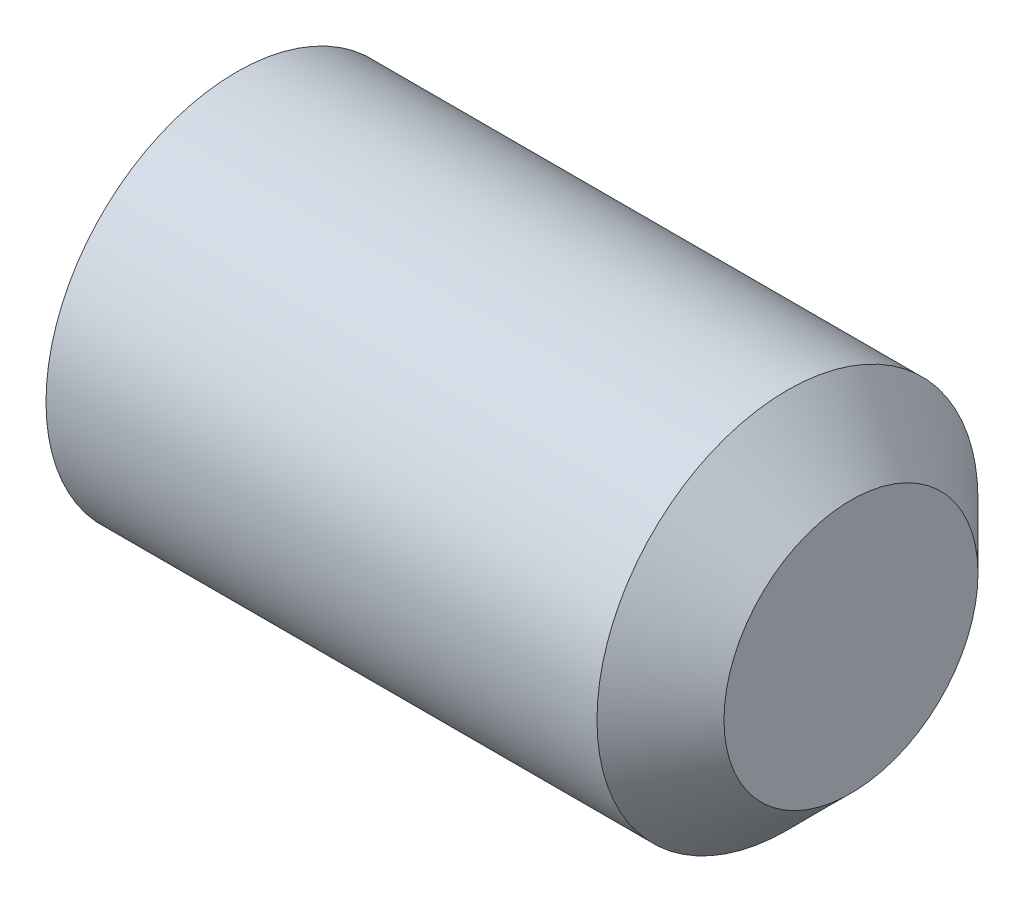
SolidWorks part; units mm, degrees
ref_plane "Plane1" through (0, 0, 0) normal (0, 0, 1) x (1, 0, 0)
ref_plane "Plane2" through (0, 0, 0) normal (0, 1, 0) x (1, 0, 0)
ref_plane "Plane3" through (0, 0, 0) normal (1, 0, 0) x (0, 0, -1)
sketch "BodySke" plane through (0, 0, 0) normal (0, 0, 1) x (1, 0, 0)
  line L0 (0, 0) -> (0, 1.2195)
  line L1 (0, 1.2195) -> (0.1619, 1.5)
  line L2 (0.1619, 1.5) -> (4.5, 1.5)
  line L3 (4.5, 1.5) -> (5, 1)
  line L4 (5, 0) -> (0, 0)
  line L5 (-12.7, 0) -> (88.9, 0) construction
  line L6 (5, 1) -> (5, 0)
  line L7 (5, 1) -> (5, 10.525) construction
  line L8 (0, -1.2195) -> (0.1619, -1.5) construction
  line L9 (0.5, 15.875) -> (0.5, -3.175) construction
  line L10 (4.5, -1.5) -> (5, -1) construction
  dimension "Length" = 5
  dimension "Diameter" = 3
  dimension "Drive_ch_ang" = 60
  dimension "Minor_dia" = 2.439
  dimension "Cup_nose_ang" = 45
  dimension "Cup_dia" = 2
  dimension "Advance" = 0.5
revolve "BaseBody" add sketch "BodySke" angle 360 about L5
cosmetic thread "ThreadCosmetic" [suppressed] parameters "Thread_minor"=2.439
sketch "Sketch2" plane through (0, 0, 0) normal (-1, 0, 0) x (0, 0, 1)
  line L0 (0.433, 0.75) -> (-0.433, 0.75)
  line L1 (-0.433, 0.75) -> (-0.866, 0)
  line L2 (0.433, 0.75) -> (0.866, 0)
  line L3 (0.433, -0.75) -> (0.866, 0)
  line L4 (0.433, -0.75) -> (-0.433, -0.75)
  line L5 (-0.433, -0.75) -> (-0.866, 0)
  dimension "Hex_size" = 1.5
  dimension "D2" = 0.75
  dimension "D3" = 0.75
extrude "Hex" cut sketch "Sketch2" against normal blind 2.1
sketch "Sketch4" plane through (0, 4.7709, -0.5249) normal (-1, 0, 0) x (0, 0, 1)
  line L0 (0.5249, -4.7709) -> (1.3124, -4.7709)
  line L1 (0.5249, -4.7709) -> (6.6732, -1.2211) construction
  line L2 (0.5249, -4.7709) -> (0.9186, -4.0889)
  line L3 (1.153, -4.6137) -> (1.2782, -4.5415)
  line L4 (0.975, -4.3054) -> (1.1002, -4.2332)
  arc A0 (1.153, -4.6137) -> (0.975, -4.3054) centre (0.5249, -4.7709) ccw
  arc A1 (1.3124, -4.7709) -> (1.2782, -4.5415) centre (0.5249, -4.7709) ccw
  arc A2 (0.9186, -4.0889) -> (1.1002, -4.2332) centre (0.5249, -4.7709) cw
  circle A3 centre (0.5249, -4.7709) radius 0.6475 construction
  circle A4 centre (0.5249, -4.7709) radius 0.7875 construction
  dimension "D1" = 30
  dimension "Spline_n_dim" = 1.295
  dimension "Spline_m_dim" = 1.575
  dimension "Spline_a_dim" = 60
  dimension "D3" = 0.178
  dimension "Spline_p_dim" = 0.356
extrude "Spline6" [suppressed] cut sketch "Sketch4" against normal blind 1.2
pattern_circular "CirPattern1" [suppressed] count 6 every 60 about axis through (-12.7, 0, 0) along (1, 0, 0)
sketch "Sketch5" plane through (0, 0.6556, 6.6316) normal (-1, 0, 0) x (0, 0, 1)
  line L0 (-6.6316, -0.6556) -> (-5.8441, -0.6556)
  line L1 (-6.6316, -0.6556) -> (-1.6115, 4.3645) construction
  line L2 (-6.6316, -0.6556) -> (-6.6316, 0.1319)
  line L3 (-6.0479, -0.3236) -> (-5.9633, -0.239)
  line L4 (-6.2996, -0.0719) -> (-6.215, 0.0127)
  line L5 (-6.2996, -0.0719) -> (-6.0479, -0.3236)
  arc A1 (-5.8441, -0.6556) -> (-5.9633, -0.239) centre (-6.6316, -0.6556) ccw
  arc A2 (-6.6316, 0.1319) -> (-6.215, 0.0127) centre (-6.6316, -0.6556) cw
  circle A3 centre (-6.6316, -0.6556) radius 0.6475 construction
  circle A4 centre (-6.6316, -0.6556) radius 0.7875 construction
  dimension "D1" = 45
  dimension "Spline_n_dim" = 1.295
  dimension "Spline_m_dim" = 1.575
  dimension "Spline_a_dim" = 90
  dimension "D3" = 0.178
  dimension "Spline_p_dim" = 0.356
extrude "Spline4" [suppressed] cut sketch "Sketch5" against normal blind 1.2
pattern_circular "CirPattern2" [suppressed] count 4 every 90 about axis through (-12.7, 0, 0) along (1, 0, 0)
sketch "ThdSchSke" plane through (0, 0, 0) normal (0, 0, 1) x (1, 0, 0)
  line L0 (0.1619, -1.2195) -> (-0.0345, -1.5)
  line L1 (0.1619, -1.2195) -> (0.3584, -1.5)
  line L2 (0.3584, -1.5) -> (0.3584, -1.875)
  line L3 (-3.175, 0) -> (5.1513, 0) construction
  line L4 (0.1619, 1.5) -> (0.1619, -1.5) construction
  line L5 (0.3584, -1.875) -> (-0.0345, -1.875)
  line L6 (-0.0345, -1.875) -> (-0.0345, -1.5)
  dimension "Thread_minor" = 2.439
  dimension "Diameter" = 3
  dimension "SideAngle" = 55
  dimension "VeeAngle" = 70
  dimension "Overcut" = 3.75
revolve "ThreadSchematic" [suppressed] cut sketch "ThdSchSke" angle 360 about L3
pattern_linear "ThdSchPat" [suppressed]
equation "\"D2@Sketch2\" = \"Hex_size@Sketch2\" / 2"
equation "\"D3@Sketch2\" = \"Hex_size@Sketch2\" / 2"
equation "\"Thread_minor@ThreadCosmetic\" = \"Minor_dia@BodySke\""
equation "\"D1@Sketch4\" = \"Spline_a_dim@Sketch4\" / 2"
equation "\"D3@Sketch4\" = \"Spline_p_dim@Sketch4\" / 2"
equation "\"D2@CirPattern1\" = \"Spline_a_dim@Sketch4\""
equation "\"Num_teeth@CirPattern1\" = 360 / \"D2@CirPattern1\""
equation "\"Spline_a_dim@Sketch5\" = 90"
equation "\"Spline_p_dim@Sketch5\" = \"Spline_p_dim@Sketch4\""
equation "\"Spline_m_dim@Sketch5\" = \"Spline_m_dim@Sketch4\""
equation "\"Spline_n_dim@Sketch5\" = \"Spline_n_dim@Sketch4\""
equation "\"D1@Sketch5\" = \"Spline_a_dim@Sketch5\" / 2"
equation "\"D3@Sketch5\" = \"Spline_p_dim@Sketch5\" / 2"
equation "\"Key_eng@Spline4\" = \"Key_eng@Spline6\""
equation "\"Thread_minor@ThdSchSke\" = \"Thread_minor@ThreadCosmetic\""
equation "\"Diameter@ThdSchSke\" = \"Diameter@BodySke\""
equation "\"Overcut@ThdSchSke\" = \"Diameter@BodySke\" * 1.25"
equation "\"Num_threads@ThdSchPat\" = int( (\"Length@BodySke\" - ( ( ( \"Diameter@BodySke\" - \"Minor_dia@BodySke\" ) * 0.5 ) / tan( \"Drive_ch_ang@BodySke\" * 0.017453292 ) ) - ( ( ( \"Diameter@BodySke\" - \"Cup_dia@BodySke\" ) * 0.5 ) * tan( \"Cup_nose_ang@BodySke\" * 0.017453292 ) ) ) / \"Advance@BodySke\" + 0.999 )  + 1"
equation "\"Advance@ThdSchPat\" = (\"Length@BodySke\" - ( ( ( \"Diameter@BodySke\" - \"Minor_dia@BodySke\" ) * 0.5 ) / tan( \"Drive_ch_ang@BodySke\" * 0.017453292 ) ) - ( ( ( \"Diameter@BodySke\" - \"Cup_dia@BodySke\" ) * 0.5 ) * tan( \"Cup_nose_ang@BodySke\" * 0.017453292 ) ) ) /  (\"Num_threads@ThdSchPat\" - 1) 'relax it"
equation "' \"Num_threads@ThdSchPat\" = \"Num_threads@ThdSchPat\" - sgn( \"Num_threads@ThdSchPat\" - 1) '---chamfered tips only---"
